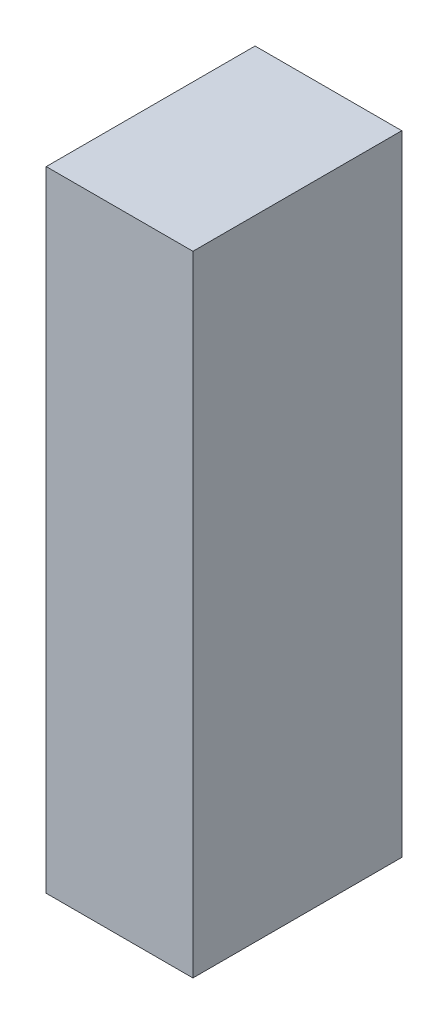
SolidWorks part; units mm, degrees
ref_plane "Plan de face" through (0, 0, 0) normal (0, 0, 1) x (1, 0, 0)
ref_plane "Plan de dessus" through (0, 0, 0) normal (0, 1, 0) x (1, 0, 0)
ref_plane "Plan de droite" through (0, 0, 0) normal (1, 0, 0) x (0, 0, -1)
sketch "Esquisse1" plane through (0, 0, 0) normal (0, 0, 1) x (1, 0, 0)
  line L1 (0, 0) -> (7.0241, 0)
  line L2 (0, 0) -> (0, 30.1352)
  line L3 (0, 30.1352) -> (7.0241, 30.1352)
  line L4 (7.0241, 0) -> (7.0241, 30.1352)
extrude "Extrusion1" add sketch "Esquisse1" along normal blind 10
